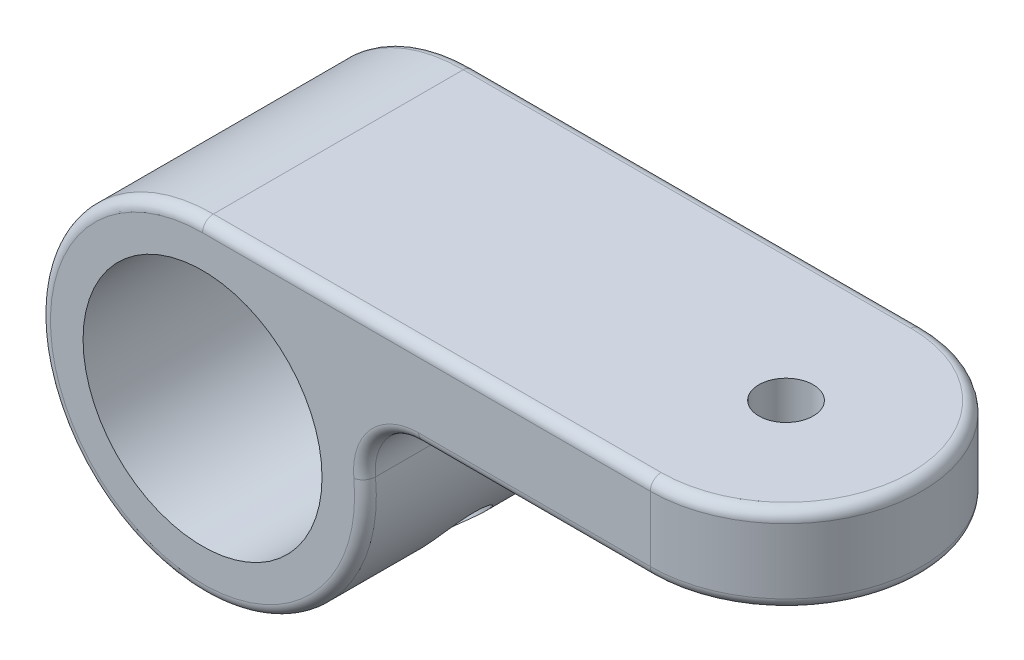
SolidWorks part; units mm, degrees
material "5052-H34"
ref_plane "Plano frontal" through (0, 0, 0) normal (0, 0, 1) x (1, 0, 0)
ref_plane "Plano superior" through (0, 0, 0) normal (0, 1, 0) x (1, 0, 0)
ref_plane "Plano direito" through (0, 0, 0) normal (1, 0, 0) x (0, 0, -1)
sketch "Esboço1" plane through (0, 0, 0) normal (0, 0, 1) x (1, 0, 0)
  circle A0 centre (0, 0) radius 15
  dimension "D1" = 30
extrude "Ressalto-extrusão1" add sketch "Esboço1" along normal mid plane 25
ref_plane "Plano1" through (0, 15, 0) normal (0, 1, 0) x (1, 0, 0)
sketch "Esboço2" plane through (0, 15, 0) normal (0, 1, 0) x (1, 0, 0)
  line L0 (0, 0) -> (41.219, 0) construction
  line L2 (41.219, 12.5) -> (0, 12.5)
  line L5 (0, 12.5) -> (0, -12.5)
  line L6 (-15, -12.5) -> (15, -12.5) construction
  line L7 (0, -12.5) -> (41.219, -12.5)
  arc A0 (41.219, -12.5) -> (41.219, 12.5) centre (41.219, 0) ccw
  dimension "D1" = 25
  dimension "D2" = 53.719
  dimension "D3" = 25
extrude "Ressalto-extrusão2" add sketch "Esboço2" against normal blind 8
fillet "Filete1" radius 5 1 edges at (13.2665, 7, 0)
sketch "Esboço3" plane through (0, 0, -12.5) normal (0, 0, -1) x (-1, 0, 0)
  circle A0 centre (0, 0) radius 11
  dimension "D1" = 22
extrude "Corte-extrusão1" cut sketch "Esboço3" against normal through all
ref_plane "Plano2" through (10.6066, -10.6066, 0) normal (0.7071, -0.7071, 0) x (0, 0, -1)
sketch "Esboço6" plane through (10.6066, -10.6066, 0) normal (0.7071, -0.7071, 0) x (0, 0, -1)
  circle A0 centre (0, 0) radius 3
  dimension "D1" = 6
extrude "Corte-extrusão2" cut sketch "Esboço6" against normal up to next
hole_wizard "Furo roscado de M62" positions "Esboço7" profile "Esboço8" tap size "M6" standard "DIN" end condition through all
sketch "Esboço7" plane through (0, 15, 0) normal (0, 1, 0) x (1, 0, 0)
  point P0 (41.219, 0)
sketch "Esboço8" plane through (41.219, 15, 0) normal (1, 0, 0) x (0, 0, 1)
  line L0 (0, 0) -> (0, 30)
  line L1 (0, 30) -> (2.5, 30)
  line L2 (2.5, 30) -> (2.5, 0)
  line L5 (2.5, 0) -> (0, 0)
  line L11 (0, -6.35) -> (0, 107.95) construction
  dimension "Thru Tap Drill Dia." = 5
  dimension "Thru Tap Drill Depth" = 30
cosmetic thread "Rosca de furo2" parameters "D2"=6
fillet "Filete2" radius 1 10 edges at (20.6095, 15, -12.5) (53.719, 15, 0) (20.6095, 15, 12.5) (-10.0623, -11.1243, 12.5) (16.1916, 5.3541, 12.5) (30.5594, 7, 12.5) (53.719, 7, 0) (30.5594, 7, -12.5) (16.1916, 5.3541, -12.5) (-10.0623, -11.1243, -12.5)
